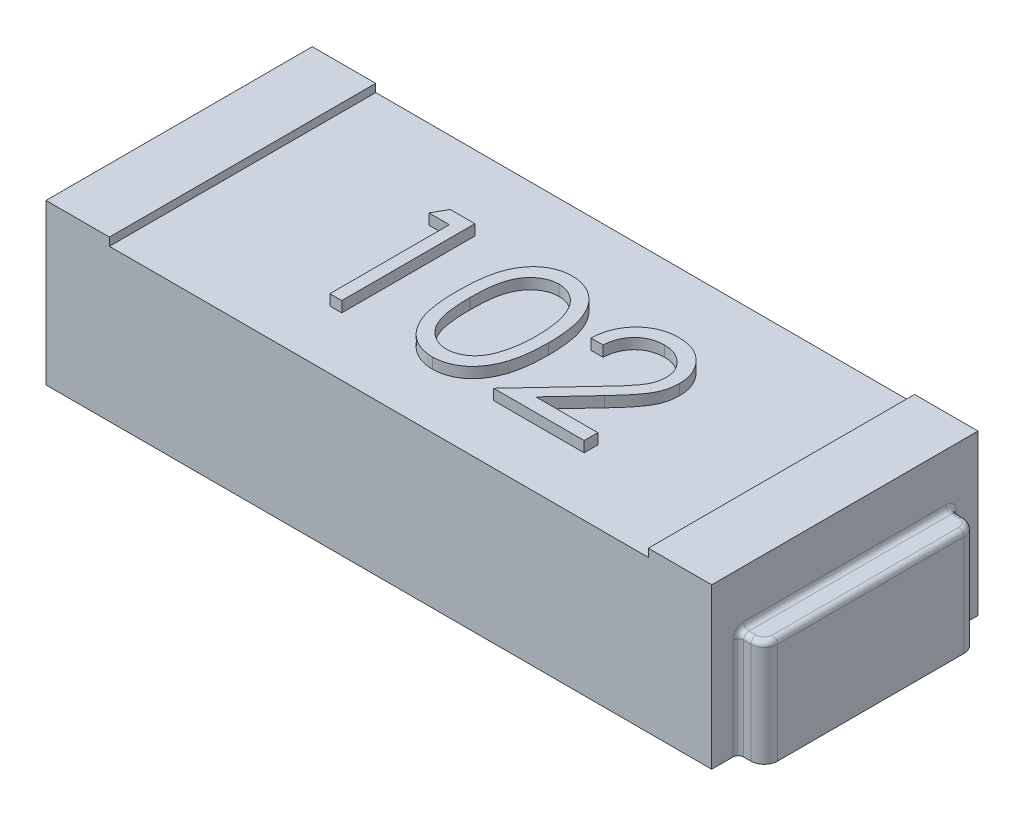
SolidWorks part; units mm, degrees
ref_plane "Plan de face" through (0, 0, 0) normal (0, 0, 1) x (1, 0, 0)
ref_plane "Plan de dessus" through (0, 0, 0) normal (0, 1, 0) x (1, 0, 0)
ref_plane "Plan de droite" through (0, 0, 0) normal (1, 0, 0) x (0, 0, -1)
sketch "Esquisse1" plane through (0, 0, 0) normal (0, 1, 0) x (1, 0, 0)
  line L1 (1.25, -0.5) -> (-1.25, -0.5)
  line L2 (1.25, -0.5) -> (1.25, 0.5)
  line L3 (1.25, 0.5) -> (-1.25, 0.5)
  line L4 (-1.25, -0.5) -> (-1.25, 0.5)
  line L5 (1.25, -0.5) -> (-1.25, 0.5) construction
  line L6 (1.25, 0.5) -> (-1.25, -0.5) construction
  point P0 (0, 0)
  dimension "D1" = 2.5
  dimension "D2" = 1
extrude "Boss.-Extru.1" add sketch "Esquisse1" along normal blind 0.6
sketch "Esquisse2" plane through (0, 0.6, 0) normal (0, 1, 0) x (1, 0, 0)
  line L0 (1.25, 0.5) -> (-1.25, 0.5) construction
  line L1 (1.0118, -0.5) -> (-1.0118, -0.5)
  line L2 (1.0118, -0.5) -> (1.0118, 0.5)
  line L3 (1.0118, 0.5) -> (-1.0118, 0.5)
  line L4 (-1.0118, -0.5) -> (-1.0118, 0.5)
  line L5 (1.0118, -0.5) -> (-1.0118, 0.5) construction
  line L6 (1.0118, 0.5) -> (-1.0118, -0.5) construction
  point P0 (0, 0)
extrude "Enlèv. mat.-Extru.1" cut sketch "Esquisse2" against normal blind 0.03
sketch "Esquisse3" plane through (0, 0, 0) normal (0, 1, 0) x (1, 0, 0)
  line L0 (1.25, -0.5) -> (1.25, 0.5) construction
  line L1 (1.25, 0.4) -> (1.2971, 0.4)
  line L2 (1.25, 0.4) -> (1.25, -0.4)
  line L3 (1.25, -0.4) -> (1.2971, -0.4)
  line L4 (1.3471, 0.35) -> (1.3471, -0.35)
  line L5 (1.25, 0.5) -> (1.0118, 0.5) construction
  line L6 (1.0118, -0.5) -> (1.25, -0.5) construction
  arc A0 (1.2971, -0.4) -> (1.3471, -0.35) centre (1.2971, -0.35) ccw
  arc A1 (1.2971, 0.4) -> (1.3471, 0.35) centre (1.2971, 0.35) cw
  dimension "D1" = 0.05
  dimension "D2" = 0.1
  dimension "D3" = 0.1
extrude "Boss.-Extru.2" add sketch "Esquisse3" along normal blind 0.4
fillet "Congé1" radius 0.02 8 edges at (1.25, 0.2, -0.4) (1.25, 0.2, 0.4) (1.2736, 0.4, -0.4) (1.3325, 0.4, -0.3854) (1.3471, 0.4, 0) (1.3325, 0.4, 0.3854) (1.2736, 0.4, 0.4) (1.25, 0.4, 0)
mirror "Symétrie2" about plane through (0, 0, 0) normal (1, 0, 0) of "Congé1", "Boss.-Extru.2"
sketch "Esquisse4" plane through (0, 0.57, 0) normal (0, 1, 0) x (1, 0, 0)
  line L0 (0.7576, -0.2803) -> (-0.7576, -0.2803) construction
  text T0 "102\r\n" font "Century Gothic" height 0.5
  point P3 (0, -0.2803)
extrude "Boss.-Extru.3" add sketch "Esquisse4" along normal blind 0.04
